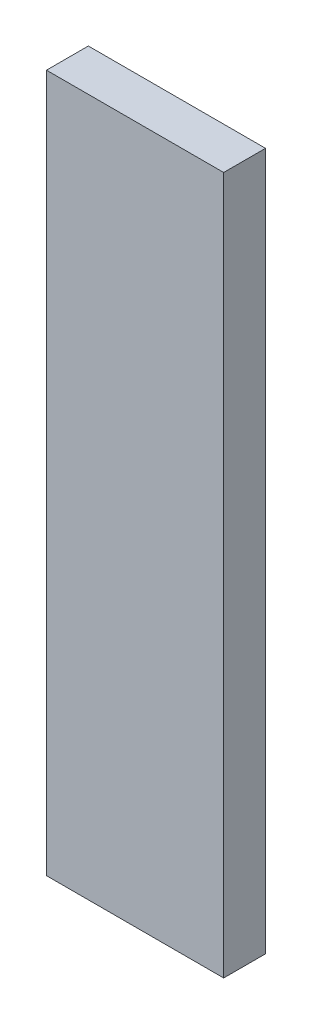
SolidWorks part; units mm, degrees
ref_plane "Front Plane" through (0, 0, 0) normal (0, 0, 1) x (1, 0, 0)
ref_plane "Top Plane" through (0, 0, 0) normal (0, 1, 0) x (1, 0, 0)
ref_plane "Right Plane" through (0, 0, 0) normal (1, 0, 0) x (0, 0, -1)
sketch "Sketch1" plane through (0, 0, 0) normal (0, 0, 1) x (1, 0, 0)
  line L1 (-3.175, -12.5) -> (3.175, -12.5)
  line L2 (-3.175, -12.5) -> (-3.175, 12.5)
  line L3 (-3.175, 12.5) -> (3.175, 12.5)
  line L4 (3.175, -12.5) -> (3.175, 12.5)
  line L5 (-3.175, -12.5) -> (3.175, 12.5) construction
  line L6 (-3.175, 12.5) -> (3.175, -12.5) construction
  point P0 (0, 0)
  dimension "D1" = 25
  dimension "D2" = 6.35
extrude "Boss-Extrude1" add sketch "Sketch1" along normal blind 1.5
